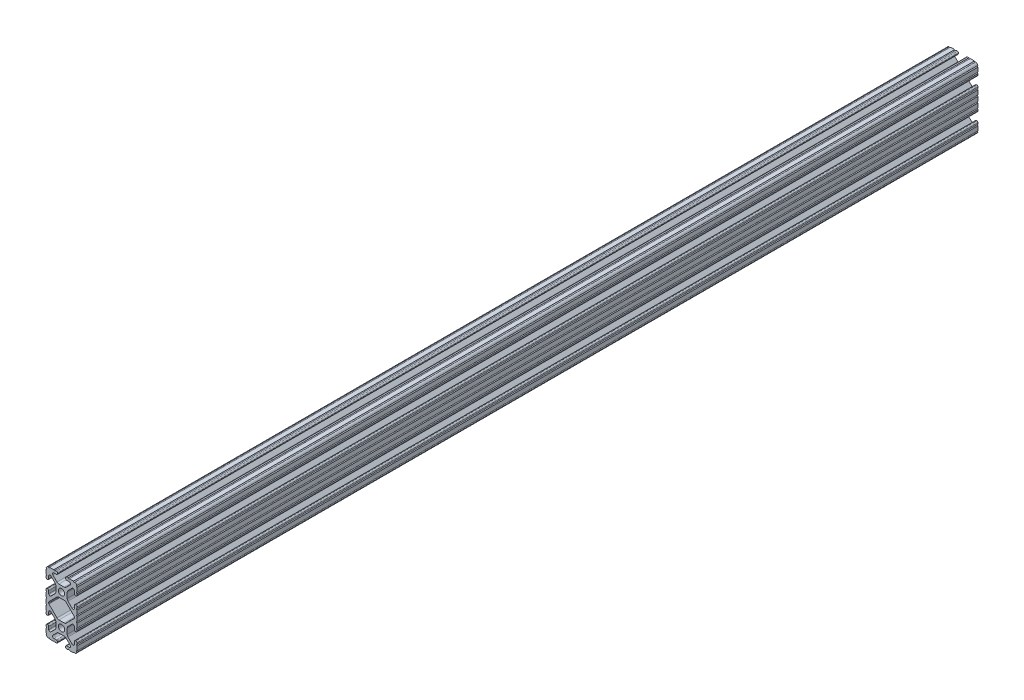
SolidWorks part; units mm, degrees
ref_plane "Front Plane" through (0, 0, 0) normal (0, 0, 1) x (1, 0, 0)
ref_plane "Top Plane" through (0, 0, 0) normal (0, 1, 0) x (1, 0, 0)
ref_plane "Right Plane" through (0, 0, 0) normal (1, 0, 0) x (0, 0, -1)
sketch "Sketch2" plane through (0, 0, 0) normal (0, 0, 1) x (1, 0, 0)
  line L0 (0, 25.4) -> (0, -25.4) construction
  line L1 (-12.7, 0) -> (12.7, 0) construction
  line L2 (3.2512, -25.4) -> (12.7, -25.4)
  line L3 (12.7, -25.4) -> (12.7, -15.9512)
  line L4 (3.2512, -25.4) -> (3.2512, -23.1902)
  line L5 (3.2512, -23.1902) -> (8.9276, -23.1902)
  line L6 (8.9276, -23.1902) -> (3.0856, -17.3482)
  line L7 (0, -12.7) -> (12.7, -25.4) construction
  line L8 (12.7, -15.9512) -> (10.4902, -15.9512)
  line L9 (10.4902, -15.9512) -> (10.4902, -21.6276)
  line L10 (10.4902, -21.6276) -> (4.6482, -15.7856)
  line L11 (3.2512, -25.4) -> (0, -25.4) construction
  line L12 (0, -25.4) -> (-3.2512, -25.4) construction
  line L13 (-3.2512, -25.4) -> (-12.7, -25.4) construction
  line L14 (12.7, 25.4) -> (-12.7, 25.4) construction
  line L15 (0, 12.7) -> (0, -12.7) construction
  circle A0 centre (0, -12.7) radius 2.6035
  arc A1 (6.3485, -23.1902) -> (7.1039, -21.3665) centre (6.3485, -22.1219) ccw construction
  point P8 (0, -17.3482)
  point P16 (-2.6035, -12.7)
  point P18 (2.6035, -12.7)
  point P19 (0, -10.0965)
  point P20 (0, -15.3035)
  point P27 (-12.7, -25.4)
  point P30 (0, 25.4)
  point P31 (12.7, 25.4)
  point P32 (-12.7, 25.4)
  point P33 (12.7, -25.4)
  point P34 (0, -12.7)
  point P35 (0, 12.7)
  point P37 (0, 0)
  point P38 (-3.2512, -25.4)
  point P39 (3.2512, -25.4)
  dimension "Center Hole Diameter" = 5.207
  dimension "Rail Height" = 50.8
  dimension "Rail Width" = 25.4
  dimension "T-Slot Width" = 6.5024
  dimension "Slot Inner Width" = 14.8336
  dimension "Thickness" = 2.2098
  dimension "Slot Depth" = 5.842
  dimension "D1" = 2.2098
  dimension "C to C" = 25.4
sketch "Sketch3" plane through (0, 0, 0) normal (1, 0, 0) x (0, 0, -1)
  line L0 (-457.2, -25.4) -> (457.2, -25.4) construction
  line L1 (-406.4, 0) -> (406.4, 0) construction
  point P6 (-457.2, -25.4)
  point P8 (-406.4, 0)
  point P9 (406.4, 0)
  point P10 (457.2, -25.4)
  dimension "Length" = 914.4
  dimension "D1" = 50.8
sketch "Sketch4" plane through (0, 0, 0) normal (0, 0, 1) x (1, 0, 0)
  line L0 (4.1904, -25.4) -> (10.1173, -25.4)
  line L1 (3.2512, -25.4) -> (12.7, -25.4) construction
  line L2 (3.2512, -25.4) -> (3.2512, -23.1902) construction
  line L3 (3.2512, -23.1902) -> (8.9276, -23.1902) construction
  line L4 (3.2512, -24.1294) -> (3.2512, -24.4608)
  line L5 (4.1904, -23.1902) -> (6.3485, -23.1902)
  line L6 (0, -17.3482) -> (2.164, -17.3482)
  line L7 (8.9276, -23.1902) -> (3.0856, -17.3482) construction
  line L8 (3.7373, -17.9999) -> (7.1039, -21.3665)
  line L9 (12.7, -25.4) -> (12.7, -15.9512) construction
  line L10 (10.4902, -21.6276) -> (4.6482, -15.7856) construction
  line L11 (10.4902, -15.9512) -> (10.4902, -21.6276) construction
  line L12 (10.4902, -19.0485) -> (10.4902, -16.8904)
  line L13 (12.7, -15.9512) -> (10.4902, -15.9512) construction
  line L14 (11.4294, -15.9512) -> (11.7608, -15.9512)
  line L15 (12.7, -16.8904) -> (12.7, -22.8173)
  line L16 (8.6665, -19.8039) -> (5.2999, -16.4373)
  line L17 (4.6482, -12.7) -> (4.6482, -14.864)
  line L19 (0, -17.3482) -> (0, -15.3035)
  line L20 (0, 25.4) -> (0, -25.4) construction
  line L21 (4.6482, -12.7) -> (2.6035, -12.7)
  arc A0 (3.2512, -24.4608) -> (4.1904, -25.4) centre (4.1904, -24.4608) ccw
  circle A1 centre (0, -12.7) radius 2.6035 construction
  arc A2 (3.2512, -24.1294) -> (4.1904, -23.1902) centre (4.1904, -24.1294) cw
  arc A3 (6.3485, -23.1902) -> (7.1039, -21.3665) centre (6.3485, -22.1219) ccw
  arc A4 (2.164, -17.3482) -> (3.7373, -17.9999) centre (2.164, -19.5732) cw
  arc A5 (10.1173, -25.4) -> (12.7, -22.8173) centre (10.1173, -22.8173) ccw
  arc A6 (8.6665, -19.8039) -> (10.4902, -19.0485) centre (9.4219, -19.0485) ccw
  arc A7 (10.4902, -16.8904) -> (11.4294, -15.9512) centre (11.4294, -16.8904) cw
  arc A8 (11.7608, -15.9512) -> (12.7, -16.8904) centre (11.7608, -16.8904) cw
  arc A9 (5.2999, -16.4373) -> (4.6482, -14.864) centre (6.8732, -14.864) cw
  arc A11 (0, -15.3035) -> (2.6035, -12.7) centre (0, -12.7) ccw
  dimension "D1" = 2.5827
  dimension "D2" = 2.225
  dimension "D3" = 0.9392
extrude "Boss-Extrude1" add sketch "Sketch4" along normal mid plane 914.4
sketch "Sketch5" plane through (0, 0, 0) normal (0, 0, 1) x (1, 0, 0)
  line L0 (3.2512, -25.4) -> (12.7, -25.4) construction
  line L1 (4.1904, -23.1902) -> (6.3485, -23.1902) construction
  line L3 (0, -12.7) -> (12.7, -25.4) construction
  line L4 (6.3485, -23.1902) -> (6.3485, -25.4) construction
  line L5 (8.9276, -23.1902) -> (3.0856, -17.3482) construction
  circle A0 centre (10.3562, -25.4) radius 0.5524
  circle A1 centre (5.796, -25.4) radius 0.5524
  circle A2 centre (12.7, -23.0562) radius 0.5524
  circle A3 centre (12.7, -18.496) radius 0.5524
  point P10 (5.2694, -23.1902)
  point P12 (9.4219, -19.0485)
  dimension "D1" = 1.1049
extrude "Cut-Extrude1" cut sketch "Sketch5" against normal through all both and the other way through all
mirror "Mirror1" about plane through (4.6482, -12.7, 457.2) normal (0, -1, 0) of bodies 137 134
sketch "Sketch6" plane through (0, 0, 0) normal (0, 0, 1) x (1, 0, 0)
  line L0 (12.7, -1.7914) -> (12.7, 0)
  line L1 (12.7, 0) -> (9.8037, 0)
  line L2 (-12.7, 0) -> (12.7, 0) construction
  line L3 (9.8037, 0) -> (9.8037, -2.3438)
  line L4 (9.8037, -2.3438) -> (12.1476, -2.3438)
  circle A0 centre (12.7, -2.3438) radius 0.5524 construction
  arc A1 (12.7, -1.7914) -> (12.1476, -2.3438) centre (12.7, -2.3438) ccw
  arc A4 (12.58, -1.8046) -> (12.7, -2.8963) centre (12.7, -2.3438) ccw construction
  arc A6 (9.8037, 0) -> (10.8954, -0.12) centre (10.3562, 0) ccw construction
extrude "Boss-Extrude2" add sketch "Sketch6" along normal mid plane 914.4
sketch "Sketch7" plane through (0, 0, 0) normal (0, 0, 1) x (1, 0, 0)
  line L0 (5.4206, -5.7168) -> (10.3284, -0.809)
  line L1 (3.7373, -7.4001) -> (7.1039, -4.0335) construction
  line L2 (10.4902, -0.4184) -> (10.4902, 0)
  line L3 (0, 0) -> (10.4902, 0)
  line L4 (-12.7, 0) -> (12.7, 0) construction
  line L5 (0, 0) -> (5.4206, -5.7168)
  arc A0 (10.3284, -0.809) -> (10.4902, -0.4184) centre (9.9377, -0.4184) ccw
  arc A3 (12.7, -1.7914) -> (12.7, -2.8963) centre (12.7, -2.3438) ccw construction
extrude "Cut-Extrude2" cut sketch "Sketch7" against normal through all both and the other way through all
mirror "Mirror2" about plane through (0, 0, 0) normal (0, 1, 0) of bodies 139 135
mirror "Mirror3" about plane through (0, 0, 0) normal (1, 0, 0) of bodies 136
sketch "Sketch8" plane through (0, 0, 457.2) normal (0, 0, 1) x (1, 0, 0)
  line L1 (-15.7498, 26.461) -> (16.0317, 26.461)
  line L2 (-15.7498, 26.461) -> (-15.7498, -27.7295)
  line L3 (-15.7498, -27.7295) -> (16.0317, -27.7295)
  line L4 (16.0317, 26.461) -> (16.0317, -27.7295)
extrude "Cut-Extrude3" cut sketch "Sketch8" against normal blind 177.8
equation "\"D1@Boss-Extrude1\"=\"Length@Sketch3\""
equation "\"D1@Sketch2\"=\"Thickness@Sketch2\""
equation "\"D2@Sketch4\"=\"Slot Inner Width@Sketch2\"*0.15"
equation "\"D1@Sketch4\"=\"D3@Sketch4\"*2.75"
equation "\"D3@Sketch4\"=\"Thickness@Sketch2\"*0.425"
equation "\"D1@Sketch5\"=\"Thickness@Sketch2\"*0.5"
equation "\"D1@Boss-Extrude2\"=\"Length@Sketch3\""
